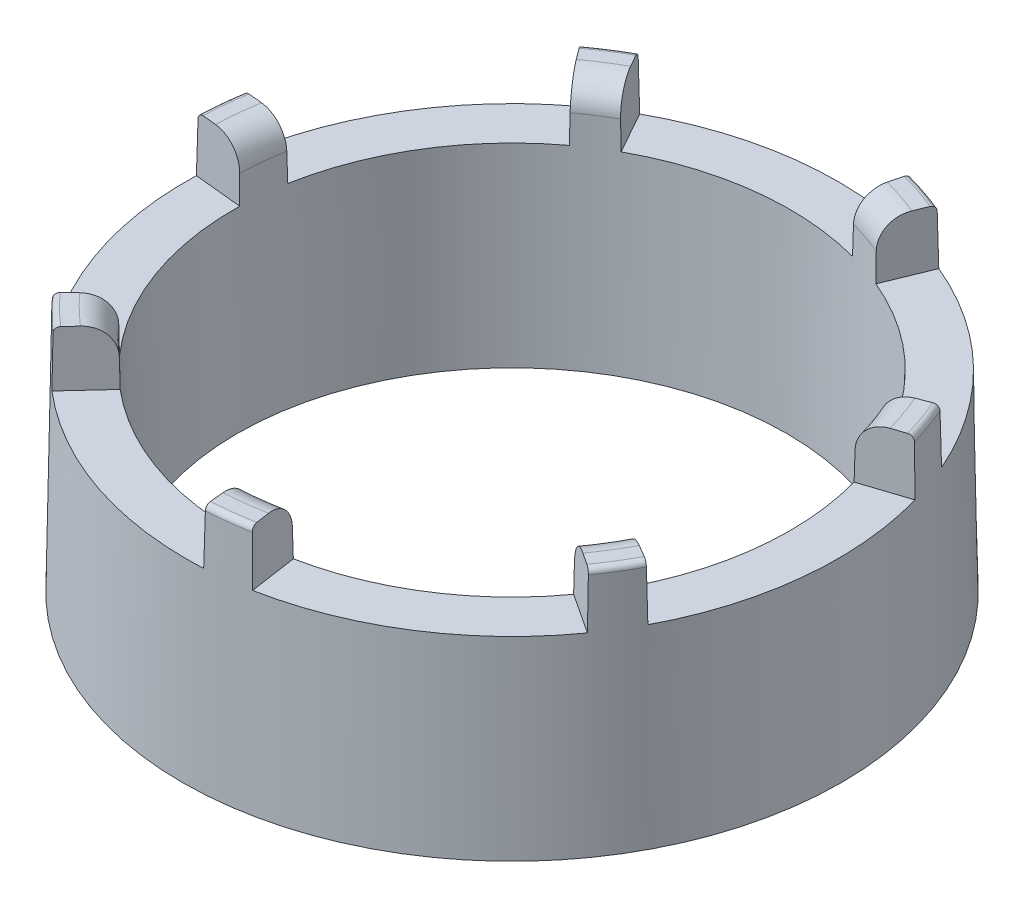
SolidWorks part; units mm, degrees
ref_plane "Front Plane" through (0, 0, 0) normal (0, 0, 1) x (1, 0, 0)
ref_plane "Top Plane" through (0, 0, 0) normal (0, 1, 0) x (1, 0, 0)
ref_plane "Right Plane" through (0, 0, 0) normal (1, 0, 0) x (0, 0, -1)
sketch "Sketch8" plane through (0, 0, 0) normal (0, 1, 0) x (1, 0, 0)
  line L0 (-6.7142, -0.9334) -> (-6.3049, -0.9334)
  line L1 (-8.4775, -0.9334) -> (-8.0682, -0.9334)
  line L2 (4.2485, 3.8281) -> (3.8797, 3.6505)
  line L3 (5.8372, 4.5931) -> (5.4684, 4.4155)
  line L4 (-0.4502, 6.3214) -> (-0.5413, 5.9223)
  line L5 (-0.0578, 8.0405) -> (-0.1489, 7.6414)
  line L6 (-5.329, 4.2023) -> (-5.0738, 3.8823)
  line L7 (-6.4285, 5.5809) -> (-6.1732, 5.2608)
  line L8 (-0.0125, -2.1158) -> (0.3968, -2.1158)
  line L9 (-1.7758, -2.1158) -> (-1.3665, -2.1158)
  line L10 (6.8173, -2.1652) -> (6.4485, -1.9875)
  line L11 (5.2287, -1.4) -> (4.8599, -1.2224)
  line L12 (1.7523, -5.426) -> (1.6612, -5.027)
  line L13 (2.1446, -7.1451) -> (2.0535, -6.7461)
  line L14 (-3.5629, -5.2182) -> (-3.3076, -4.8982)
  line L15 (-4.6623, -6.5968) -> (-4.4071, -6.2768)
  line L16 (-0.6895, 0.2298) -> (-5.8187, -4.2849) construction
  circle A0 centre (-4.8682, -5.0431) radius 0.4308
  circle A1 centre (-6.7693, -3.5268) radius 0.4308
  arc A2 (-6.3049, -0.9334) -> (-4.8063, 1.4122) centre (-7.3912, 1.4122) ccw
  arc A3 (-4.8063, 1.4122) -> (-9.9761, 1.4122) centre (-7.3912, 1.4122) ccw
  arc A4 (-9.9761, 1.4122) -> (-8.4775, -0.9334) centre (-7.3912, 1.4122) ccw
  arc A5 (-9.8325, 1.4122) -> (-8.0682, -0.9334) centre (-7.3912, 1.4122) ccw
  arc A6 (-4.9499, 1.4122) -> (-9.8325, 1.4122) centre (-7.3912, 1.4122) ccw
  arc A7 (-6.7142, -0.9334) -> (-4.9499, 1.4122) centre (-7.3912, 1.4122) ccw
  circle A8 centre (-1.5693, -6.8784) radius 0.4308
  circle A9 centre (0.8015, -6.3374) radius 0.4308
  arc A10 (4.2485, 3.8281) -> (3.6765, 0.9493) centre (5.8761, 2.0085) ccw
  arc A11 (3.6765, 0.9493) -> (8.0757, 3.0677) centre (5.8761, 2.0085) ccw
  arc A12 (8.0757, 3.0677) -> (5.4684, 4.4155) centre (5.8761, 2.0085) ccw
  arc A13 (8.2051, 3.13) -> (5.8372, 4.5931) centre (5.8761, 2.0085) ccw
  arc A14 (3.5471, 0.887) -> (8.2051, 3.13) centre (5.8761, 2.0085) ccw
  arc A15 (3.8797, 3.6505) -> (3.5471, 0.887) centre (5.8761, 2.0085) ccw
  circle A16 centre (-4.8679, 5.4359) radius 0.4308
  circle A17 centre (-2.9667, 6.9521) radius 0.4308
  arc A18 (-0.5413, 5.9223) -> (1.412, 3.9393) centre (1.9873, 6.4594) ccw
  arc A19 (1.412, 3.9393) -> (2.5625, 8.9795) centre (1.9873, 6.4594) ccw
  arc A20 (2.5625, 8.9795) -> (-0.0578, 8.0405) centre (1.9873, 6.4594) ccw
  arc A21 (2.5305, 8.8395) -> (-0.1489, 7.6414) centre (1.9873, 6.4594) ccw
  arc A22 (1.444, 4.0793) -> (2.5305, 8.8395) centre (1.9873, 6.4594) ccw
  arc A23 (-0.4502, 6.3214) -> (1.444, 4.0793) centre (1.9873, 6.4594) ccw
  arc A24 (-5.0738, 3.8823) -> (-2.3056, 4.1731) centre (-3.9173, 6.194) ccw
  arc A25 (-2.3056, 4.1731) -> (-5.529, 8.215) centre (-3.9173, 6.194) ccw
  arc A26 (-5.529, 8.215) -> (-6.4285, 5.5809) centre (-3.9173, 6.194) ccw
  arc A27 (-5.4395, 8.1027) -> (-6.1732, 5.2608) centre (-3.9173, 6.194) ccw
  arc A28 (-2.3951, 4.2854) -> (-5.4395, 8.1027) centre (-3.9173, 6.194) ccw
  arc A29 (-5.329, 4.2023) -> (-2.3951, 4.2854) centre (-3.9173, 6.194) ccw
  circle A30 centre (0.8019, 6.73) radius 0.4308
  circle A31 centre (3.1726, 6.1888) radius 0.4308
  circle A32 centre (5.3484, -2.7116) radius 0.4308
  circle A33 centre (6.4036, 0.913) radius 0.4308
  arc A34 (-3.2744, 0.2298) -> (-1.7758, -2.1158) centre (-0.6895, 0.2298) ccw
  arc A35 (1.8954, 0.2298) -> (-3.2744, 0.2298) centre (-0.6895, 0.2298) ccw
  arc A36 (0.3968, -2.1158) -> (1.8954, 0.2298) centre (-0.6895, 0.2298) ccw
  arc A37 (-0.0125, -2.1158) -> (1.7518, 0.2298) centre (-0.6895, 0.2298) ccw
  arc A38 (1.7518, 0.2298) -> (-3.1308, 0.2298) centre (-0.6895, 0.2298) ccw
  arc A39 (-3.1308, 0.2298) -> (-1.3665, -2.1158) centre (-0.6895, 0.2298) ccw
  circle A40 centre (5.3486, 3.1039) radius 0.4308
  circle A41 centre (-7.3912, 2.6281) radius 0.4308
  circle A42 centre (-7.3912, 0.1963) radius 0.4308
  circle A43 centre (-0.6895, 1.4457) radius 0.4308
  circle A44 centre (-0.6895, -0.986) radius 0.4308
  arc A45 (7.0204, -4.8664) -> (6.4485, -1.9875) centre (4.8208, -3.8071) ccw
  arc A46 (2.6213, -2.7477) -> (7.0204, -4.8664) centre (4.8208, -3.8071) ccw
  arc A47 (5.2287, -1.4) -> (2.6213, -2.7477) centre (4.8208, -3.8071) ccw
  arc A48 (4.8599, -1.2224) -> (2.4919, -2.6854) centre (4.8208, -3.8071) ccw
  arc A49 (2.4919, -2.6854) -> (7.1498, -4.9287) centre (4.8208, -3.8071) ccw
  arc A50 (7.1498, -4.9287) -> (6.8173, -2.1652) centre (4.8208, -3.8071) ccw
  circle A51 centre (4.2933, -4.9025) radius 0.4308
  arc A52 (1.7523, -5.426) -> (-0.927, -4.2278) centre (-0.3839, -6.6079) ccw
  arc A53 (-0.927, -4.2278) -> (0.1593, -8.988) centre (-0.3839, -6.6079) ccw
  arc A54 (0.1593, -8.988) -> (2.0535, -6.7461) centre (-0.3839, -6.6079) ccw
  arc A55 (0.1912, -9.1281) -> (2.1446, -7.1451) centre (-0.3839, -6.6079) ccw
  arc A56 (-0.959, -4.0878) -> (0.1912, -9.1281) centre (-0.3839, -6.6079) ccw
  arc A57 (1.6612, -5.027) -> (-0.959, -4.0878) centre (-0.3839, -6.6079) ccw
  arc A58 (-3.3076, -4.8982) -> (-4.2069, -2.264) centre (-5.8187, -4.2849) ccw
  arc A59 (-4.2069, -2.264) -> (-7.4305, -6.3058) centre (-5.8187, -4.2849) ccw
  arc A60 (-7.4305, -6.3058) -> (-4.6623, -6.5968) centre (-5.8187, -4.2849) ccw
  arc A61 (-7.341, -6.1935) -> (-4.4071, -6.2768) centre (-5.8187, -4.2849) ccw
  arc A62 (-4.2965, -2.3763) -> (-7.341, -6.1935) centre (-5.8187, -4.2849) ccw
  arc A63 (-3.5629, -5.2182) -> (-4.2965, -2.3763) centre (-5.8187, -4.2849) ccw
  circle A64 centre (-0.6895, 0.2298) radius 10
  circle A65 centre (-0.6895, 0.2298) radius 12
extrude "Boss-Extrude5" add sketch "Sketch8" along normal blind 7 draft 1 contours A65 A64
sketch "Sketch9" plane through (0, 7, 0) normal (0, 1, 0) x (1, 0, 0)
  line L0 (5.3486, 3.1039) -> (6.4036, 0.913) construction
  line L1 (5.8761, 2.0085) -> (10.4937, 4.2321) construction
  line L2 (3.1726, 6.1888) -> (0.8019, 6.73) construction
  line L3 (-2.9667, 6.9521) -> (-4.8679, 5.4359) construction
  line L4 (-7.3912, 2.6281) -> (-7.3912, 0.1963) construction
  line L5 (-6.7693, -3.5268) -> (-4.8682, -5.0431) construction
  line L6 (-1.5693, -6.8784) -> (0.8015, -6.3374) construction
  line L7 (5.3484, -2.7116) -> (4.2933, -4.9025) construction
  line L8 (4.8208, -3.8071) -> (9.4122, -6.0183) construction
  line L9 (-0.3839, -6.6079) -> (0.7464, -11.5609) construction
  line L10 (-5.8187, -4.2849) -> (-8.9923, -8.264) construction
  line L11 (-7.3912, 1.4122) -> (-12.5083, 1.4122) construction
  line L12 (-3.9173, 6.194) -> (-7.1233, 10.2142) construction
  line L13 (1.9873, 6.4594) -> (3.1323, 11.476) construction
  line L14 (-5.5811, 9.0916) -> (-6.4367, 10.6247)
  line L15 (-10.6504, 2.0299) -> (-12.4019, 2.2051)
  line L16 (3.2159, 9.5683) -> (3.8807, 11.1932)
  line L17 (9.0673, 2.925) -> (10.7378, 3.4702)
  line L18 (7.5009, -5.718) -> (8.9687, -6.6841)
  line L19 (-0.2192, -9.8814) -> (-0.0505, -11.6308)
  line L20 (-8.282, -6.4644) -> (-9.5453, -7.6858)
  line L21 (-6.7271, 8.3543) -> (-7.7808, 9.7585)
  line L22 (-10.8095, 0.4387) -> (-12.5611, 0.6139)
  line L23 (1.9261, 10.0082) -> (2.3666, 11.7077)
  line L24 (8.5619, 4.3373) -> (10.199, 4.9758)
  line L25 (8.2899, -4.4423) -> (9.8098, -5.3241)
  line L26 (1.2808, -9.6987) -> (1.5368, -11.4375)
  line L27 (-7.2093, -7.5129) -> (-8.4018, -8.8036)
  line L28 (-8.282, -6.4644) -> (-7.2093, -7.5129) construction
  line L29 (8.2899, -4.4423) -> (7.5009, -5.718) construction
  line L30 (9.8098, -5.3241) -> (8.9687, -6.6841) construction
  line L31 (-0.2192, -9.8814) -> (1.2808, -9.6987) construction
  line L32 (8.5619, 4.3373) -> (9.0673, 2.925) construction
  line L33 (-10.6504, 2.0299) -> (-10.8095, 0.4387) construction
  circle A14 centre (-0.6895, 0.2298) radius 10.1222 construction
  circle A15 centre (-0.6895, 0.2298) radius 11.8778
  arc A16 (-12.4019, 2.2051) -> (-12.5611, 0.6139) centre (-0.6895, 0.2298) ccw
  arc A17 (-10.6504, 2.0299) -> (-10.8095, 0.4387) centre (-0.6895, 0.2298) ccw
  arc A18 (-5.5811, 9.0916) -> (-6.7271, 8.3543) centre (-0.6895, 0.2298) ccw
  arc A19 (3.2159, 9.5683) -> (1.9261, 10.0082) centre (-0.6895, 0.2298) ccw
  arc A20 (7.5009, -5.718) -> (8.2899, -4.4423) centre (-0.6895, 0.2298) ccw
  arc A21 (9.0673, 2.925) -> (8.5619, 4.3373) centre (-0.6895, 0.2298) ccw
  arc A22 (-0.2192, -9.8814) -> (1.2808, -9.6987) centre (-0.6895, 0.2298) ccw
  arc A23 (-8.282, -6.4644) -> (-7.2093, -7.5129) centre (-0.6895, 0.2298) ccw
  arc A24 (3.8807, 11.1932) -> (2.3666, 11.7077) centre (-0.6895, 0.2298) ccw
  arc A25 (-6.4367, 10.6247) -> (-7.7808, 9.7585) centre (-0.6895, 0.2298) ccw
  arc A26 (10.7378, 3.4702) -> (10.199, 4.9758) centre (-0.6895, 0.2298) ccw
  arc A27 (8.9687, -6.6841) -> (9.8098, -5.3241) centre (-0.6895, 0.2298) ccw
  arc A28 (-0.0505, -11.6308) -> (1.5368, -11.4375) centre (-0.6895, 0.2298) ccw
  arc A29 (-9.5453, -7.6858) -> (-8.4018, -8.8036) centre (-0.6895, 0.2298) ccw
  circle A30 centre (-7.3912, 2.6281) radius 0.4308 construction
  circle A31 centre (-7.3912, 0.1963) radius 0.4308 construction
  circle A32 centre (-6.7693, -3.5268) radius 0.4308 construction
  circle A33 centre (-4.8682, -5.0431) radius 0.4308 construction
  circle A34 centre (-1.5693, -6.8784) radius 0.4308 construction
  circle A35 centre (0.8015, -6.3374) radius 0.4308 construction
  circle A36 centre (4.2933, -4.9025) radius 0.4308 construction
  circle A37 centre (5.3484, -2.7116) radius 0.4308 construction
  circle A38 centre (5.3486, 3.1039) radius 0.4308 construction
  circle A39 centre (6.4036, 0.913) radius 0.4308 construction
  circle A40 centre (3.1726, 6.1888) radius 0.4308 construction
  circle A41 centre (0.8019, 6.73) radius 0.4308 construction
  circle A42 centre (-4.8679, 5.4359) radius 0.4308 construction
  circle A43 centre (-2.9667, 6.9521) radius 0.4308 construction
  circle A44 centre (-7.3912, 2.6281) radius 0.4308 construction
  circle A45 centre (-7.3912, 0.1963) radius 0.4308 construction
  circle A46 centre (-6.7693, -3.5268) radius 0.4308 construction
  circle A47 centre (-4.8682, -5.0431) radius 0.4308 construction
  circle A48 centre (-1.5693, -6.8784) radius 0.4308 construction
  circle A49 centre (0.8015, -6.3374) radius 0.4308 construction
  circle A50 centre (4.2933, -4.9025) radius 0.4308 construction
  circle A51 centre (5.3484, -2.7116) radius 0.4308 construction
  circle A52 centre (5.3486, 3.1039) radius 0.4308 construction
  circle A53 centre (6.4036, 0.913) radius 0.4308 construction
  circle A54 centre (3.1726, 6.1888) radius 0.4308 construction
  circle A55 centre (0.8019, 6.73) radius 0.4308 construction
  circle A56 centre (-4.8679, 5.4359) radius 0.4308 construction
  circle A57 centre (-2.9667, 6.9521) radius 0.4308 construction
  point P3 (3.1323, 11.476)
  point P5 (-12.5083, 1.4122)
  point P10 (1.9873, 6.4594)
  point P40 (0.7464, -11.5609)
  point P58 (-5.8187, -4.2849)
  point P62 (-7.3912, 1.4122)
  point P105 (-3.9173, 6.194)
  point P108 (-0.3839, -6.6079)
  point P111 (9.4122, -6.0183)
  point P112 (4.8208, -3.8071)
  point P113 (5.8761, 2.0085)
  point P114 (10.4937, 4.2321)
  point P115 (-7.1233, 10.2142)
  circle M1 centre (-0.6895, 0.2298) radius 10.1222
  circle M2 centre (-0.6895, 0.2298) radius 11.8778
  dimension "D2" = 0.8
  dimension "D4" = 0.8
  dimension "D9" = 1.5
  dimension "D3" = 0.8
  dimension "D5" = 0.8
  dimension "D6" = 1.5
  dimension "D7" = 0.8
  dimension "D8" = 0.8
  dimension "D10" = 0.8
  dimension "D11" = 0.8
  dimension "D1" = 0
extrude "Boss-Extrude7" add sketch "Sketch9" along normal blind 2 draft 1 contours L27 L20 M1 M2 | L22 L15 M1 M2 | L21 L14 M1 M2 | L23 L16 M1 M2 | L24 L17 M1 M2 | L25 L18 M1 M2 | L26 L19 M1 M2
fillet "Fillet3" radius 0.2 7 edges at (-8.9679, 9, 8.239) (0.7422, 9, 11.5262) (9.3825, 9, 5.9999) (10.4609, 9, -4.2203) (3.1213, 9, -11.4429) (-7.1043, 9, -10.185) (-12.4736, 9, -1.4087)
fillet "Fillet4" radius 1 7 edges at (-6.1855, 9, -8.7715) (-10.7961, 9, -1.2409) (-7.7895, 9, 7.0335) (0.5384, 9, 9.8528) (7.9487, 9, 5.1131) (8.8736, 9, -3.6523) (2.5894, 9, -9.8431)
sketch "Sketch3" plane through (0, 0, 0) normal (0, 1, 0) x (1, 0, 0)
  line L0 (-6.0247, -1.1632) -> (-5.6154, -1.1632)
  line L1 (-7.788, -1.1632) -> (-7.3787, -1.1632)
  line L8 (4.938, 3.5982) -> (4.5692, 3.4206)
  line L9 (6.5267, 4.3633) -> (6.1579, 4.1857)
  line L10 (0.2393, 6.0915) -> (0.1482, 5.6924)
  line L11 (0.6317, 7.8106) -> (0.5406, 7.4115)
  line L12 (-4.6395, 3.9725) -> (-4.3843, 3.6524)
  line L13 (-5.739, 5.3511) -> (-5.4837, 5.031)
  line L14 (0.677, -2.3456) -> (1.0863, -2.3456)
  line L15 (-1.0863, -2.3456) -> (-0.677, -2.3456)
  line L16 (7.5069, -2.395) -> (7.138, -2.2174)
  line L17 (5.9182, -1.6299) -> (5.5494, -1.4523)
  line L18 (2.4418, -5.6559) -> (2.3507, -5.2568)
  line L19 (2.8341, -7.375) -> (2.743, -6.9759)
  line L20 (-2.8734, -5.4481) -> (-2.6181, -5.1281)
  line L21 (-3.9728, -6.8266) -> (-3.7176, -6.5066)
  line L22 (0, 0) -> (-5.1292, -4.5148) construction
  circle A2 centre (-4.1787, -5.2729) radius 0.4308
  circle A3 centre (-6.0798, -3.7566) radius 0.4308
  arc A4 (-5.6154, -1.1632) -> (-4.1168, 1.1824) centre (-6.7017, 1.1824) ccw
  arc A5 (-4.1168, 1.1824) -> (-9.2866, 1.1824) centre (-6.7017, 1.1824) ccw
  arc A6 (-9.2866, 1.1824) -> (-7.788, -1.1632) centre (-6.7017, 1.1824) ccw
  arc A7 (-9.143, 1.1824) -> (-7.3787, -1.1632) centre (-6.7017, 1.1824) ccw
  arc A8 (-4.2604, 1.1824) -> (-9.143, 1.1824) centre (-6.7017, 1.1824) ccw
  arc A9 (-6.0247, -1.1632) -> (-4.2604, 1.1824) centre (-6.7017, 1.1824) ccw
  circle A10 centre (-0.8798, -7.1083) radius 0.4308
  circle A11 centre (1.491, -6.5672) radius 0.4308
  arc A12 (4.938, 3.5982) -> (4.366, 0.7194) centre (6.5656, 1.7786) ccw
  arc A13 (4.366, 0.7194) -> (8.7652, 2.8378) centre (6.5656, 1.7786) ccw
  arc A14 (8.7652, 2.8378) -> (6.1579, 4.1857) centre (6.5656, 1.7786) ccw
  arc A15 (8.8946, 2.9001) -> (6.5267, 4.3633) centre (6.5656, 1.7786) ccw
  arc A16 (4.2366, 0.6571) -> (8.8946, 2.9001) centre (6.5656, 1.7786) ccw
  arc A17 (4.5692, 3.4206) -> (4.2366, 0.6571) centre (6.5656, 1.7786) ccw
  circle A18 centre (-4.1784, 5.2061) radius 0.4308
  circle A19 centre (-2.2772, 6.7223) radius 0.4308
  arc A20 (0.1482, 5.6924) -> (2.1015, 3.7094) centre (2.6768, 6.2296) ccw
  arc A21 (2.1015, 3.7094) -> (3.252, 8.7497) centre (2.6768, 6.2296) ccw
  arc A22 (3.252, 8.7497) -> (0.6317, 7.8106) centre (2.6768, 6.2296) ccw
  arc A23 (3.22, 8.6097) -> (0.5406, 7.4115) centre (2.6768, 6.2296) ccw
  arc A24 (2.1335, 3.8494) -> (3.22, 8.6097) centre (2.6768, 6.2296) ccw
  arc A25 (0.2393, 6.0915) -> (2.1335, 3.8494) centre (2.6768, 6.2296) ccw
  arc A26 (-4.3843, 3.6524) -> (-1.6161, 3.9432) centre (-3.2278, 5.9642) ccw
  arc A27 (-1.6161, 3.9432) -> (-4.8395, 7.9852) centre (-3.2278, 5.9642) ccw
  arc A28 (-4.8395, 7.9852) -> (-5.739, 5.3511) centre (-3.2278, 5.9642) ccw
  arc A29 (-4.75, 7.8729) -> (-5.4837, 5.031) centre (-3.2278, 5.9642) ccw
  arc A30 (-1.7056, 4.0555) -> (-4.75, 7.8729) centre (-3.2278, 5.9642) ccw
  arc A31 (-4.6395, 3.9725) -> (-1.7056, 4.0555) centre (-3.2278, 5.9642) ccw
  circle A32 centre (1.4914, 6.5001) radius 0.4308
  circle A33 centre (3.8621, 5.959) radius 0.4308
  circle A34 centre (6.0379, -2.9414) radius 0.4308
  circle A35 centre (7.0931, 0.6831) radius 0.4308
  arc A36 (-2.5849, 0) -> (-1.0863, -2.3456) centre (0, 0) ccw
  arc A37 (2.5849, 0) -> (-2.5849, 0) centre (0, 0) ccw
  arc A38 (1.0863, -2.3456) -> (2.5849, 0) centre (0, 0) ccw
  arc A39 (0.677, -2.3456) -> (2.4413, 0) centre (0, 0) ccw
  arc A40 (2.4413, 0) -> (-2.4413, 0) centre (0, 0) ccw
  arc A41 (-2.4413, 0) -> (-0.677, -2.3456) centre (0, 0) ccw
  circle A42 centre (6.0381, 2.8741) radius 0.4308
  circle A43 centre (-6.7017, 2.3982) radius 0.4308
  circle A44 centre (-6.7017, -0.0335) radius 0.4308
  circle A45 centre (0, 1.2159) radius 0.4308
  circle A46 centre (0, -1.2159) radius 0.4308
  arc A47 (7.7099, -5.0962) -> (7.138, -2.2174) centre (5.5103, -4.0369) ccw
  arc A48 (3.3108, -2.9776) -> (7.7099, -5.0962) centre (5.5103, -4.0369) ccw
  arc A49 (5.9182, -1.6299) -> (3.3108, -2.9776) centre (5.5103, -4.0369) ccw
  arc A50 (5.5494, -1.4523) -> (3.1814, -2.9153) centre (5.5103, -4.0369) ccw
  arc A51 (3.1814, -2.9153) -> (7.8393, -5.1585) centre (5.5103, -4.0369) ccw
  arc A52 (7.8393, -5.1585) -> (7.5069, -2.395) centre (5.5103, -4.0369) ccw
  circle A53 centre (4.9828, -5.1323) radius 0.4308
  arc A54 (2.4418, -5.6559) -> (-0.2375, -4.4576) centre (0.3056, -6.8377) ccw
  arc A55 (-0.2375, -4.4576) -> (0.8488, -9.2179) centre (0.3056, -6.8377) ccw
  arc A56 (0.8488, -9.2179) -> (2.743, -6.9759) centre (0.3056, -6.8377) ccw
  arc A57 (0.8807, -9.3579) -> (2.8341, -7.375) centre (0.3056, -6.8377) ccw
  arc A58 (-0.2695, -4.3176) -> (0.8807, -9.3579) centre (0.3056, -6.8377) ccw
  arc A59 (2.3507, -5.2568) -> (-0.2695, -4.3176) centre (0.3056, -6.8377) ccw
  arc A60 (-2.6181, -5.1281) -> (-3.5174, -2.4939) centre (-5.1292, -4.5148) ccw
  arc A61 (-3.5174, -2.4939) -> (-6.741, -6.5357) centre (-5.1292, -4.5148) ccw
  arc A62 (-6.741, -6.5357) -> (-3.9728, -6.8266) centre (-5.1292, -4.5148) ccw
  arc A63 (-6.6515, -6.4234) -> (-3.7176, -6.5066) centre (-5.1292, -4.5148) ccw
  arc A64 (-3.607, -2.6062) -> (-6.6515, -6.4234) centre (-5.1292, -4.5148) ccw
  arc A65 (-2.8734, -5.4481) -> (-3.607, -2.6062) centre (-5.1292, -4.5148) ccw
  circle A66 centre (0, 0) radius 10
  circle A67 centre (0, 0) radius 12
  dimension "D1" = 20
  dimension "D2" = 2
